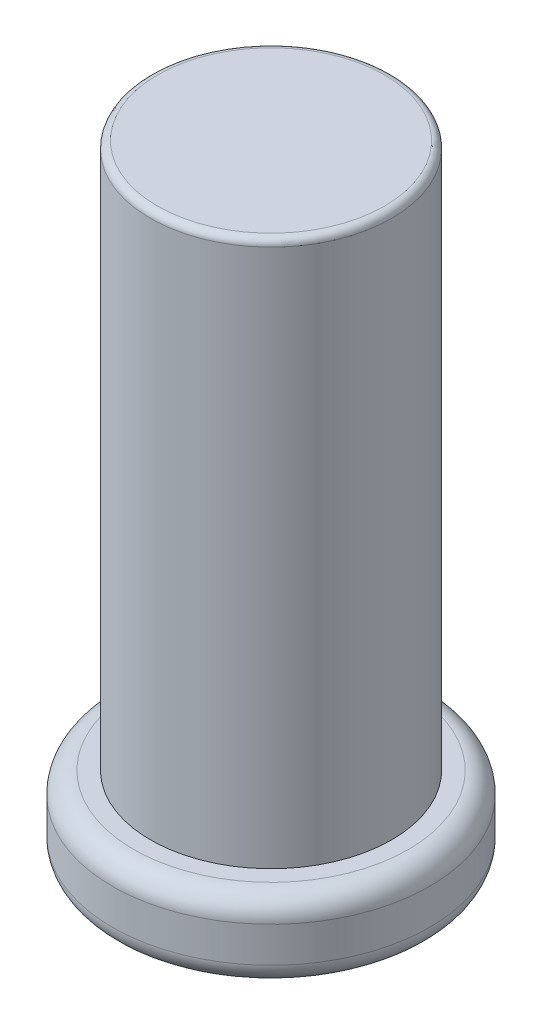
SolidWorks part; units mm, degrees
ref_plane "前视基准面" through (0, 0, 0) normal (0, 0, 1) x (1, 0, 0)
ref_plane "上视基准面" through (0, 0, 0) normal (0, 1, 0) x (1, 0, 0)
ref_plane "右视基准面" through (0, 0, 0) normal (1, 0, 0) x (0, 0, -1)
sketch "草图1" plane through (0, 0, 0) normal (0, 0, 1) x (1, 0, 0)
  line L0 (0, 76.85) -> (0, -11)
  line L1 (0, 0) -> (-22.35, 0)
  line L2 (0, 0) -> (0, -11)
  line L3 (0, -11) -> (-22.35, -11)
  line L4 (-22.35, 0) -> (-22.35, -11)
  line L5 (0, 0) -> (-17, 0)
  line L6 (0, 0) -> (0, 76.85)
  line L7 (0, 76.85) -> (-17, 76.85)
  line L8 (-17, 0) -> (-17, 76.85)
  dimension "D1" = 22.35
  dimension "D2" = 17
  dimension "D3" = 11
  dimension "D4" = 87.85
revolve "旋转1" add sketch "草图1" angle 360 about L0
fillet "圆角1" radius 3 2 edges at (-22.35, -11, 0) (-22.35, 0, 0)
fillet "圆角2" radius 1 1 edges at (-17, 76.85, 0)
